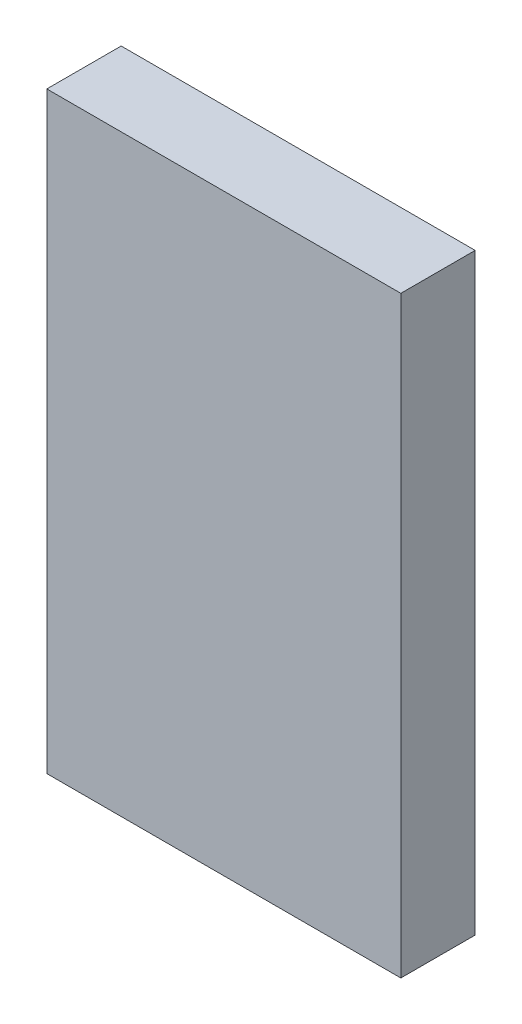
SolidWorks part; units mm, degrees
ref_plane "前视基准面" through (0, 0, 0) normal (0, 0, 1) x (1, 0, 0)
ref_plane "上视基准面" through (0, 0, 0) normal (0, 1, 0) x (1, 0, 0)
ref_plane "右视基准面" through (0, 0, 0) normal (1, 0, 0) x (0, 0, -1)
sketch "草图1" plane through (0, 0, 0) normal (0, 0, 1) x (1, 0, 0)
  line L1 (-7.6923, 4.7692) -> (12.3077, 4.7692)
  line L2 (-7.6923, 4.7692) -> (-7.6923, -28.7308)
  line L3 (-7.6923, -28.7308) -> (12.3077, -28.7308)
  line L4 (12.3077, 4.7692) -> (12.3077, -28.7308)
  dimension "D1" = 20
  dimension "D2" = 33.5
extrude "凸台-拉伸1" add sketch "草图1" along normal blind 4.2
ref_plane "基准面1" through (12.3077, 4.7692, 4.2) normal (0, 0, -1) x (-1, 0, 0)
